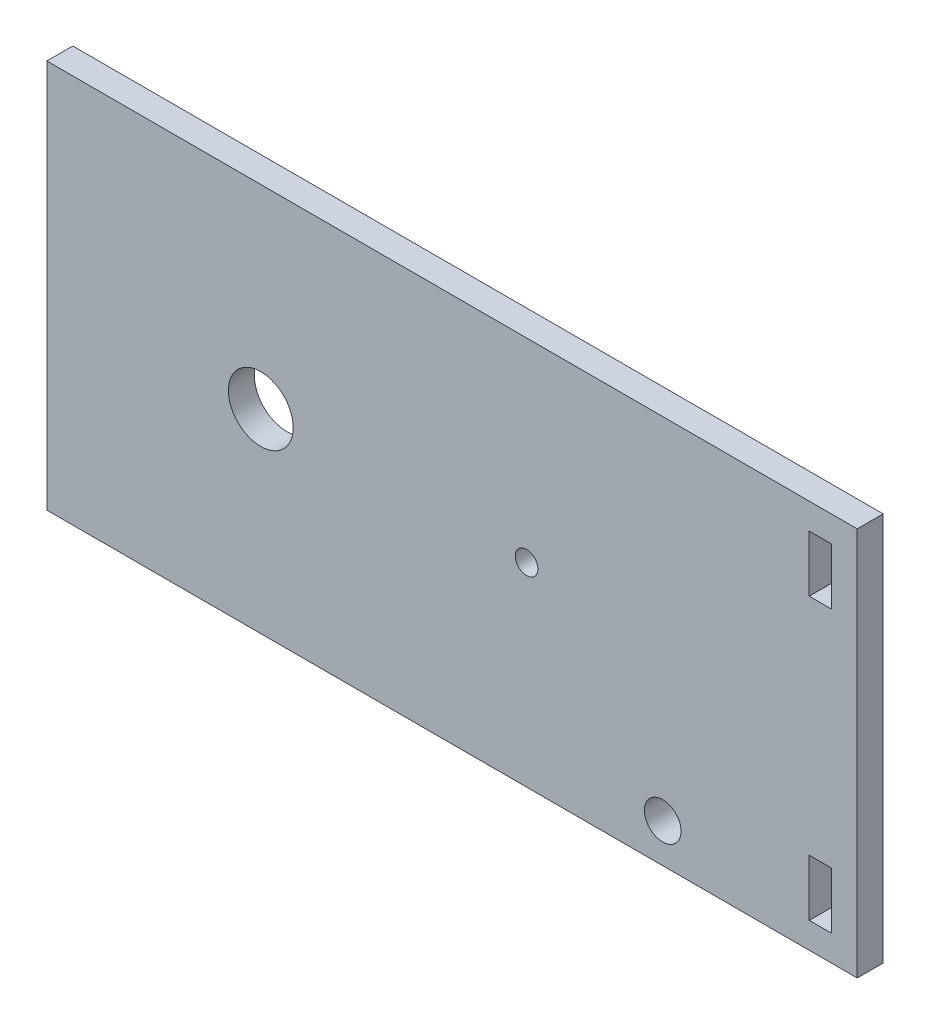
SolidWorks part; units mm, degrees
ref_plane "Front Plane" through (0, 0, 0) normal (0, 0, 1) x (1, 0, 0)
ref_plane "Top Plane" through (0, 0, 0) normal (0, 1, 0) x (1, 0, 0)
ref_plane "Right Plane" through (0, 0, 0) normal (1, 0, 0) x (0, 0, -1)
sketch "Sketch1" plane through (0, 0, 0) normal (0, 0, 1) x (1, 0, 0)
  line L1 (-81, -30) -> (40, -30)
  line L2 (-81, -30) -> (-81, 30)
  line L3 (-81, 30) -> (40, 30)
  line L11 (40, 30) -> (40, -30)
  circle A3 centre (-48, 0) radius 5
  circle A4 centre (14, -24) radius 2.83
  point P9 (-81, 0)
  dimension "D3" = 121
  dimension "D4" = 5.66
  dimension "D5" = 6
  dimension "D6" = 10
  dimension "D7" = 95
  dimension "D8" = 88
  dimension "D2" = 60
  dimension "D10" = 0
  dimension "D11" = 33
extrude "Boss-Extrude1" add sketch "Sketch1" along normal blind 4
sketch "Sketch2" plane through (0, 0, 0) normal (0, 0, 1) x (1, 0, 0)
  line L0 (40, -30) -> (44, -30)
  line L1 (44, -30) -> (44, 30)
  line L2 (44, 30) -> (40, 30)
  line L4 (40, 30) -> (-81, 30) construction
  line L16 (40, 30) -> (40, -30)
  dimension "D1" = 4
extrude "Boss-Extrude2" add sketch "Sketch2" along normal blind 4
sketch "Sketch3" plane through (0, 0, 0) normal (0, 0, 1) x (1, 0, 0)
  line L0 (40, 30) -> (40, -30) construction
  line L1 (40, 26) -> (36.6, 26)
  line L2 (40, 26) -> (40, 17.3)
  line L3 (40, 17.3) -> (36.6, 17.3)
  line L4 (36.6, 26) -> (36.6, 17.3)
  line L5 (-81, -30) -> (40, -30) construction
  line L6 (40, -17.3) -> (36.6, -17.3)
  line L7 (40, -17.3) -> (40, -26)
  line L8 (40, -26) -> (36.6, -26)
  line L9 (36.6, -17.3) -> (36.6, -26)
  line L10 (-81, 30) -> (40, 30) construction
  circle A0 centre (-7, 0) radius 1.75
  circle A1 centre (-48, 0) radius 5 construction
  point P19 (0, 0)
  dimension "D1" = 3.5
  dimension "D2" = 41
  dimension "D3" = 4
  dimension "D4" = 4
  dimension "D5" = 3.4
  dimension "D6" = 8.7
extrude "Cut-Extrude1" cut sketch "Sketch3" along normal through all both and the other way through all
equation "\"hole_width\"=3.4"
equation "\"D5@Sketch3\"=\"hole_width\""
equation "\"hole_length\"=8.7"
equation "\"D6@Sketch3\"=\"hole_length\""
